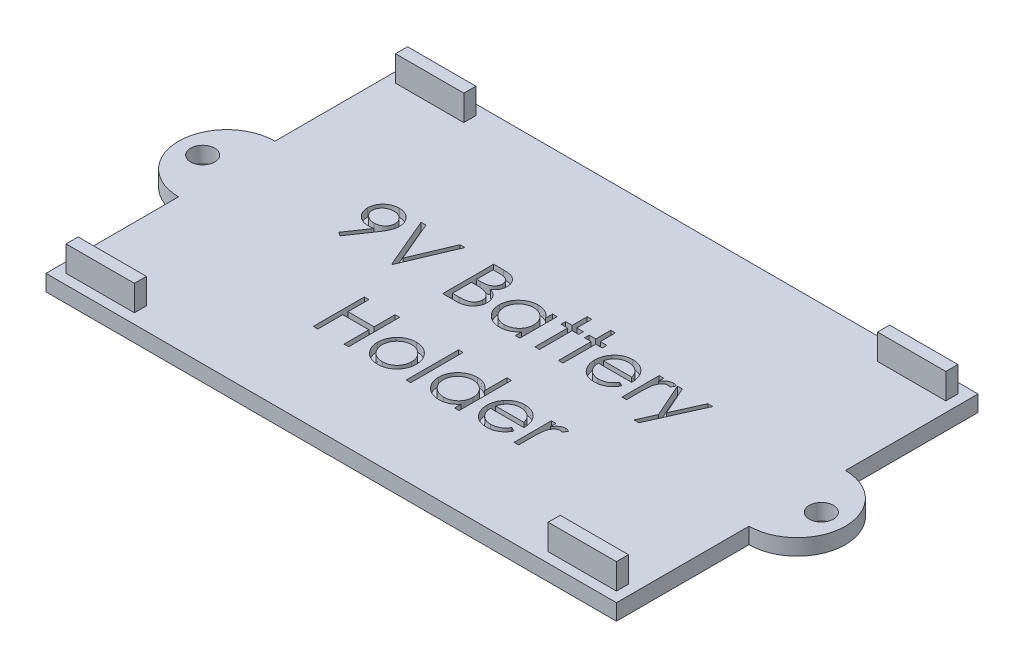
SolidWorks part; units mm, degrees
ref_plane "Front Plane" through (0, 0, 0) normal (0, 0, 1) x (1, 0, 0)
ref_plane "Top Plane" through (0, 0, 0) normal (0, 1, 0) x (1, 0, 0)
ref_plane "Right Plane" through (0, 0, 0) normal (1, 0, 0) x (0, 0, -1)
sketch "Sketch1" plane through (0, 0, 0) normal (0, 1, 0) x (1, 0, 0)
  line L1 (-35.5, -22.5) -> (35.5, -22.5)
  line L2 (-35.5, -22.5) -> (-35.5, 22.5)
  line L3 (-35.5, 22.5) -> (35.5, 22.5)
  line L4 (35.5, -22.5) -> (35.5, 22.5)
  line L5 (-35.5, -22.5) -> (35.5, 22.5) construction
  line L6 (-35.5, 22.5) -> (35.5, -22.5) construction
  point P0 (0, 0)
  dimension "D1" = 45
  dimension "D2" = 71
extrude "Boss-Extrude1" add sketch "Sketch1" along normal blind 2
sketch "Sketch2" plane through (0, 2, 0) normal (0, 1, 0) x (1, 0, 0)
  line L1 (-34.25, -21.25) -> (-25.75, -21.25)
  line L2 (-34.25, -21.25) -> (-34.25, -19.75)
  line L3 (-34.25, -19.75) -> (-25.75, -19.75)
  line L4 (-25.75, -21.25) -> (-25.75, -19.75)
  line L14 (-35.5, 22.5) -> (-35.5, -22.5) construction
  line L19 (-35.5, -22.5) -> (35.5, -22.5) construction
extrude "Boss-Extrude2" add sketch "Sketch2" along normal blind 3.175
mirror "Mirror1" about plane through (0, 0, 0) normal (0, 0, 1) of "Boss-Extrude2"
mirror "Mirror2" about plane through (0, 0, 0) normal (1, 0, 0) of "Mirror1", "Boss-Extrude2"
sketch "Sketch3" plane through (0, 2, 0) normal (0, 1, 0) x (1, 0, 0)
  line L0 (-35.5, 0) -> (35.5, 0) construction
  line L1 (-35.5, 22.5) -> (-35.5, -22.5) construction
  line L2 (35.5, -22.5) -> (35.5, 22.5) construction
  text T0 "9V Battery \r\nHolder" font "Century Gothic" height in points 24
extrude "Cut-Extrude1" cut sketch "Sketch3" against normal blind 1
sketch "Sketch4" plane through (0, 2, 0) normal (0, 1, 0) x (1, 0, 0)
  line L0 (-35.5, 22.5) -> (-35.5, -22.5) construction
  line L1 (-35.5, 6) -> (-35.5, -6)
  arc A0 (-35.5, 6) -> (-35.5, -6) centre (-35.5, 0) ccw
  dimension "D1" = 6
extrude "Boss-Extrude3" add sketch "Sketch4" against normal up to surface (2 mm away) up to face at (0, 0, 0)
sketch "Sketch5" plane through (0, 2, 0) normal (0, 1, 0) x (1, 0, 0)
  line L0 (-35.5, 22.5) -> (-35.5, 6) construction
  circle A0 centre (-38.5, 0) radius 1.5
  point P2 (0, 0)
extrude "Cut-Extrude2" cut sketch "Sketch5" against normal up to surface (2 mm away) up to face at (-12.8333, 0, 0)
mirror "Mirror3" about plane through (0, 0, 0) normal (1, 0, 0) of "Boss-Extrude3", "Cut-Extrude2"
equation "\"D4@Sketch2\"=\"D3@Sketch2\""
equation "\"Screw_Diameter\"=3"
equation "\"D1@Sketch5\"=\"Screw_Diameter\""
